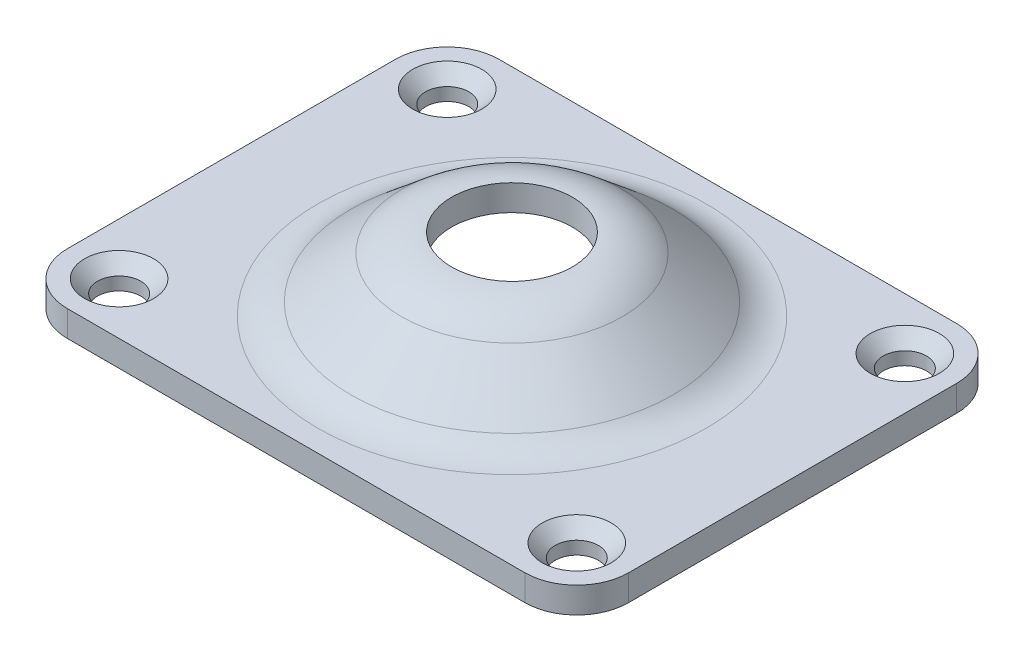
SolidWorks part; units mm, degrees
material "1023 Carbon Steel Sheet (SS)"
ref_plane "Front Plane" through (0, 0, 0) normal (0, 0, 1) x (1, 0, 0)
ref_plane "Top Plane" through (0, 0, 0) normal (0, 1, 0) x (1, 0, 0)
ref_plane "Right Plane" through (0, 0, 0) normal (1, 0, 0) x (0, 0, -1)
sketch "Sketch1" plane through (0, 0, 0) normal (0, 1, 0) x (0, 0, -1)
  line L3 (19, 32.5) -> (-19, 32.5)
  line L4 (25, 26.5) -> (25, -26.5)
  line L5 (19, -32.5) -> (-19, -32.5)
  line L6 (-25, 26.5) -> (-25, -26.5)
  line L7 (25, 32.5) -> (-25, -32.5) construction
  line L8 (25, -32.5) -> (-25, 32.5) construction
  circle A7 centre (0, 0) radius 25 construction
  circle A12 centre (-19, 26.5) radius 6 construction
  circle A13 centre (19, 26.5) radius 6 construction
  circle A14 centre (19, -26.5) radius 6 construction
  circle A15 centre (-19, -26.5) radius 6 construction
  circle A16 centre (-19, 26.5) radius 2.5
  circle A17 centre (19, 26.5) radius 2.5
  circle A18 centre (19, -26.5) radius 2.5
  circle A19 centre (-19, -26.5) radius 2.5
  arc A20 (25, -26.5) -> (19, -32.5) centre (19, -26.5) cw
  arc A21 (-19, -32.5) -> (-25, -26.5) centre (-19, -26.5) cw
  arc A22 (-19, 32.5) -> (-25, 26.5) centre (-19, 26.5) ccw
  arc A23 (19, 32.5) -> (25, 26.5) centre (19, 26.5) cw
  circle A24 centre (0, 0) radius 22.5
  point P0 (0, 0)
  dimension "D1" = 50
  dimension "D2" = 65
  dimension "D3" = 12
  dimension "D4" = 5
  dimension "D5" = 6
  dimension "D6" = 45
extrude "Boss-Extrude1" add sketch "Sketch1" along normal blind 3
sketch "Sketch2" plane through (0, 0, 0) normal (-1, 0, 0) x (0, 1, 0)
  line L0 (4.4037, 18.6433) -> (9.3193, 12.7851)
  line L1 (3, -19) -> (3, 19) construction
  line L2 (3, -22.5) -> (3, 22.5) construction
  line L8 (0, 0) -> (-7.4045, 0) construction
  line L11 (7.0212, 10.8567) -> (2.1056, 16.7149)
  line L12 (0, 22.5) -> (3, 22.5)
  line L14 (0, 21.5) -> (0, 16.5) construction
  line L18 (11.4249, 7) -> (8.4249, 7)
  line L20 (0, 25) -> (0, 19) construction
  arc A9 (2.1056, 16.7149) -> (0, 22.5) centre (9, 22.5) cw
  arc A10 (4.4037, 18.6433) -> (3, 22.5) centre (9, 22.5) cw
  arc A11 (9.3193, 12.7851) -> (11.4249, 7) centre (2.4249, 7) cw
  arc A12 (7.0212, 10.8567) -> (8.4249, 7) centre (2.4249, 7) cw
  point P24 (-10.5588, 22.1737)
  point P27 (3, 14.6263)
  dimension "D3" = 6
  dimension "D1" = 40
  dimension "D2" = 14
revolve "Revolve1" add sketch "Sketch2" angle 360 about L8
chamfer "Chamfer1" distance 1.5 angle 45 4 edges at (26.5, 3, 21.5) (26.5, 3, -16.5) (-26.5, 3, 21.5) (-26.5, 3, -16.5)
equation "\"A\"=5"
equation "\"B\"=3"
